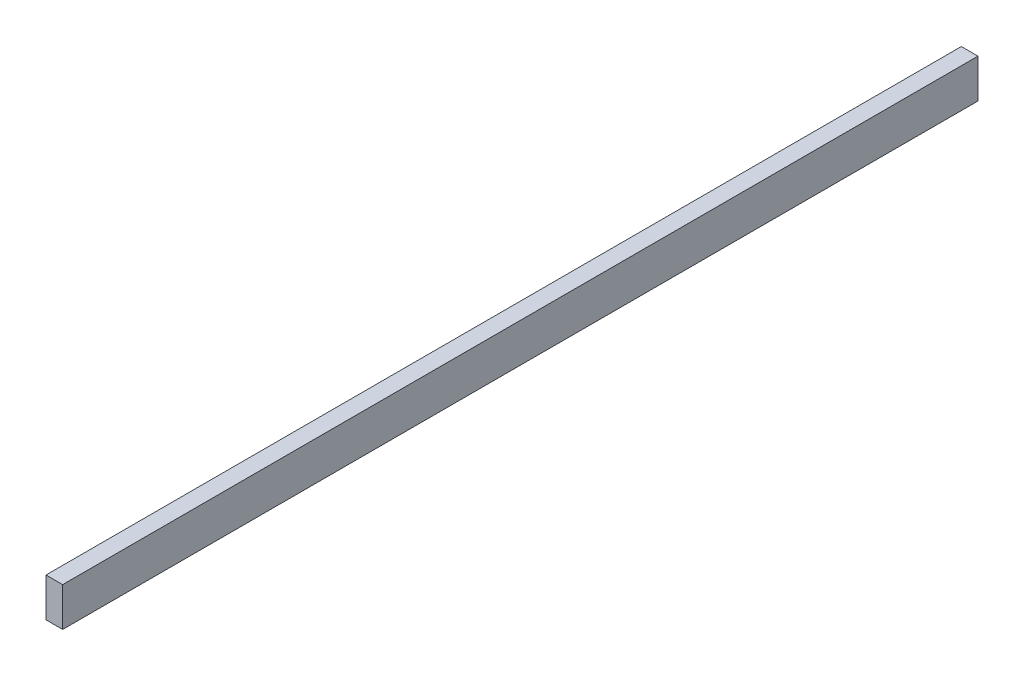
SolidWorks part; units mm, degrees
ref_plane "Front Plane" through (0, 0, 0) normal (0, 0, 1) x (1, 0, 0)
ref_plane "Top Plane" through (0, 0, 0) normal (0, 1, 0) x (1, 0, 0)
ref_plane "Right Plane" through (0, 0, 0) normal (1, 0, 0) x (0, 0, -1)
sketch "Sketch1" plane through (0, 0, 0) normal (0, 0, 1) x (1, 0, 0)
  line L1 (0, 0) -> (38.1, 0)
  line L2 (0, 0) -> (0, 88.9)
  line L3 (0, 88.9) -> (38.1, 88.9)
  line L4 (38.1, 0) -> (38.1, 88.9)
  dimension "D1" = 38.1
  dimension "D2" = 88.9
extrude "Boss-Extrude1" add sketch "Sketch1" along normal blind 2093.9125
hole_wizard "1/4 Clearance Hole1" positions "Sketch2" profile "Sketch3" hole size "1/4" standard "ANSI Inch"
sketch "Sketch2" plane through (38.1, 0, 0) normal (1, 0, 0) x (0, 0, -1)
  line L0 (-2093.9125, 44.45) -> (0, 44.45) construction
  line L1 (-2093.9125, 0) -> (-2093.9125, 88.9) construction
  line L2 (0, 0) -> (0, 88.9) construction
  line L4 (-1046.9562, 0) -> (-1046.9562, 88.9) construction
  line L5 (-2093.9125, 0) -> (0, 0) construction
  line L6 (-2093.9125, 88.9) -> (0, 88.9) construction
  line L8 (-2049.4625, 19.05) -> (-2049.4625, 69.85) construction
  line L10 (-2049.4625, 19.05) -> (-2030.4125, 44.45) construction
  line L11 (-2030.4125, 44.45) -> (-2049.4625, 69.85) construction
  point P0 (-2049.4625, 69.85)
  point P2 (-2049.4625, 19.05)
  point P4 (-2030.4125, 44.45)
  point P30 (-63.5, 44.45)
  point P31 (-44.45, 19.05)
  point P32 (-44.45, 69.85)
  dimension "D1" = 19.05
  dimension "D2" = 44.45
  dimension "D3" = 19.05
sketch "Sketch3" plane through (38.1, 69.85, 2049.4625) normal (0, 1, 0) x (0, 0, -1)
  line L0 (0, 0) -> (0, 38.1)
  line L1 (0, 38.1) -> (3.3782, 38.1)
  line L2 (3.3782, 38.1) -> (3.3782, 0)
  line L5 (3.3782, 0) -> (0, 0)
  line L11 (0, -6.35) -> (0, 107.95) construction
  dimension "Thru Hole Dia." = 6.7564
  dimension "Thru Hole Depth" = 38.1
